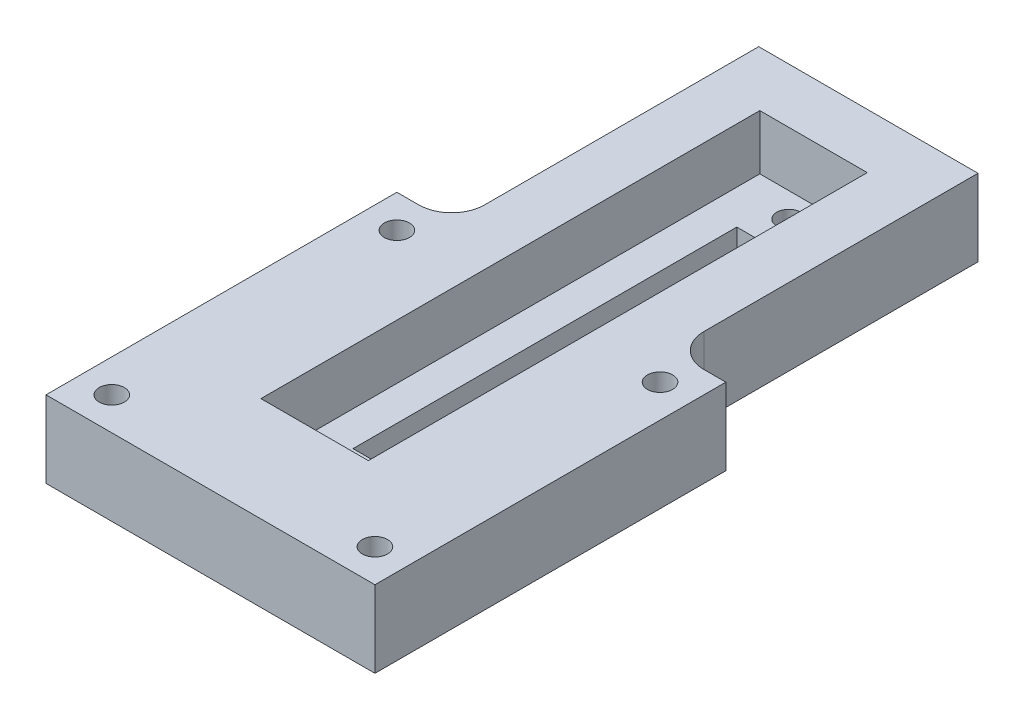
SolidWorks part; units mm, degrees
ref_plane "前视基准面" through (0, 0, 0) normal (0, 0, 1) x (1, 0, 0)
ref_plane "上视基准面" through (0, 0, 0) normal (0, 1, 0) x (1, 0, 0)
ref_plane "右视基准面" through (0, 0, 0) normal (1, 0, 0) x (0, 0, -1)
sketch "草图1" plane through (0, 0, 0) normal (0, 1, 0) x (1, 0, 0)
  line L1 (-10, -30) -> (10, -30)
  line L2 (-10, -30) -> (-10, 30)
  line L3 (-10, 30) -> (10, 30)
  line L4 (10, -30) -> (10, 30)
  line L5 (-10, -30) -> (10, 30) construction
  line L6 (-10, 30) -> (10, -30) construction
  point P0 (0, 0)
  dimension "D1" = 20
  dimension "D2" = 60
extrude "凸台-拉伸1" add sketch "草图1" along normal blind 7
sketch "草图4" plane through (0, 0, 0) normal (0, -1, 0) x (1, 0, 0)
  line L0 (0, 0) -> (0, 14) construction
  line L1 (10, -30) -> (-10, -30) construction
  line L2 (15, 30) -> (-15, 30)
  line L3 (15, 30) -> (15, -2)
  line L4 (15, -2) -> (-15, -2)
  line L5 (-15, 30) -> (-15, -2)
  line L6 (15, 30) -> (-15, -2) construction
  line L7 (15, -2) -> (-15, 30) construction
  point P7 (-31.0099, 70.116)
  point P8 (-15, 8.8658)
  dimension "D1" = 32
  dimension "D2" = 30
  dimension "D3" = 28
extrude "凸台-拉伸2" add sketch "草图4" against normal blind 7
sketch "草图3" plane through (0, 7, 0) normal (0, 1, 0) x (1, 0, 0)
  line L0 (0, 0) -> (0, 2.25) construction
  line L1 (10, 30) -> (-10, 30) construction
  line L2 (-4.9, -20.5) -> (4.9, -20.5)
  line L3 (-4.9, -20.5) -> (-4.9, 25)
  line L4 (-4.9, 25) -> (4.9, 25)
  line L5 (4.9, -20.5) -> (4.9, 25)
  line L6 (-4.9, -20.5) -> (4.9, 25) construction
  line L7 (-4.9, 25) -> (4.9, -20.5) construction
  point P7 (4.75, 29.0224)
  dimension "D1" = 45.5
  dimension "D2" = 9.8
  dimension "D3" = 5
extrude "切除-拉伸1" cut sketch "草图3" against normal blind 5
sketch "草图5" plane through (0, 2, 0) normal (0, 1, 0) x (1, 0, 0)
  line L0 (4.9, 25) -> (-4.9, 25) construction
  line L1 (4.9, 25) -> (-4.9, 25) construction
  line L2 (-4.9, -20.5) -> (4.9, -20.5) construction
  line L3 (-4.9, -20.5) -> (4.9, -20.5) construction
  line L4 (0, 25) -> (0, -20.5) construction
  line L6 (-1.75, -15.25) -> (1.75, -15.25)
  line L7 (-1.75, -15.25) -> (-1.75, 19.75)
  line L8 (-1.75, 19.75) -> (1.75, 19.75)
  line L9 (1.75, -15.25) -> (1.75, 19.75)
  line L10 (-1.75, -15.25) -> (1.75, 19.75) construction
  line L11 (-1.75, 19.75) -> (1.75, -15.25) construction
  point P6 (0, 2.25)
  dimension "D1" = 35
  dimension "D2" = 3.5
extrude "切除-拉伸2" cut sketch "草图5" against normal through all
sketch "草图6" plane through (0, 2, 0) normal (0, 1, 0) x (1, 0, 0)
  line L0 (1.75, 2.25) -> (22.039, 2.25) construction
  line L1 (1.75, -15.25) -> (1.75, 19.75) construction
  line L2 (0, 25) -> (0, -20.5) construction
  line L3 (4.9, 25) -> (-4.9, 25) construction
  line L4 (-4.9, -20.5) -> (4.9, -20.5) construction
  circle A0 centre (0, 22.75) radius 1.1
  circle A1 centre (0, -18.25) radius 1.1
  dimension "D1" = 2.2
  dimension "D2" = 41
extrude "切除-拉伸3" cut sketch "草图6" against normal through all
sketch "草图7" plane through (0, 7, 0) normal (0, 1, 0) x (1, 0, 0)
  line L0 (0, 0) -> (0, -9.3052) construction
  line L1 (-15, 2) -> (-10, 2) construction
  line L2 (-15, -30) -> (-15, 2) construction
  line L12 (15, -14) -> (-28.4578, -14) construction
  line L13 (15, 2) -> (15, -30) construction
  circle A0 centre (-12, -1) radius 1.15
  circle A1 centre (12, -1) radius 1.15
  circle A2 centre (12, -27) radius 1.15
  circle A3 centre (-12, -27) radius 1.15
  dimension "D1" = 2.3
  dimension "D2" = 3
  dimension "D3" = 3
extrude "切除-拉伸4" cut sketch "草图7" against normal through all
fillet "圆角1" radius 3 2 edges at (10, 3.5, -2) (-10, 3.5, -2)
sketch "草图8" plane through (0, 0, 0) normal (0, -1, 0) x (1, 0, 0)
  circle A0 centre (0, 18.25) radius 1.95
  circle A1 centre (0, -22.75) radius 1.95
  dimension "D1" = 3.9
extrude "切除-拉伸5" cut sketch "草图8" against normal blind 1
